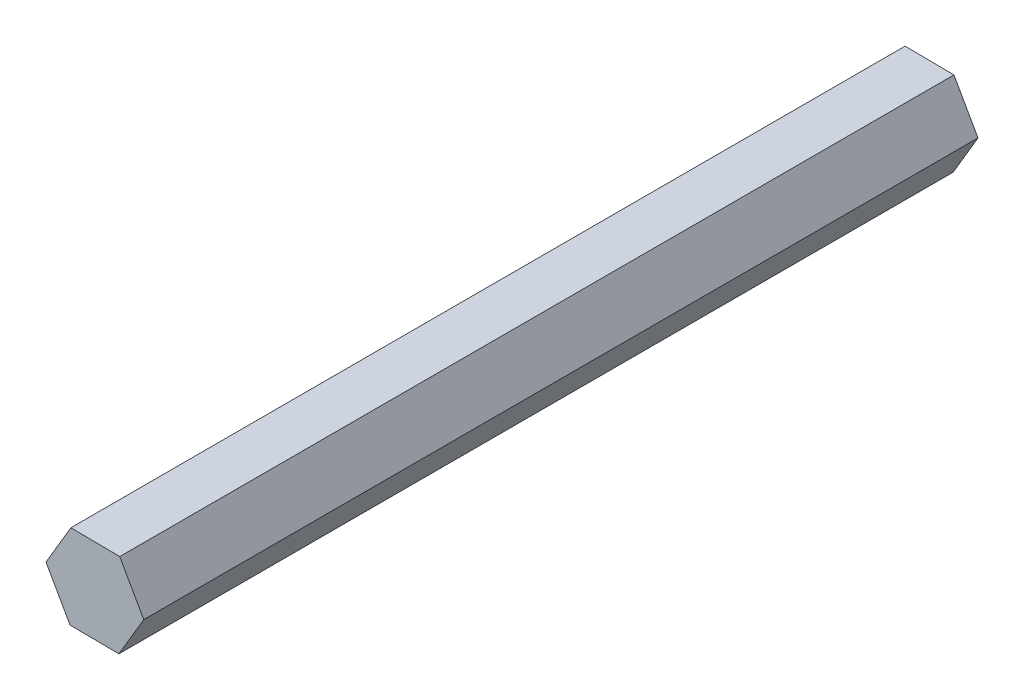
SolidWorks part; units mm, degrees
ref_plane "Front Plane" through (0, 0, 0) normal (0, 0, 1) x (1, 0, 0)
ref_plane "Top Plane" through (0, 0, 0) normal (0, 1, 0) x (1, 0, 0)
ref_plane "Right Plane" through (0, 0, 0) normal (1, 0, 0) x (0, 0, -1)
sketch "Sketch1" plane through (0, 0, 0) normal (0, 0, 1) x (1, 0, 0)
  line L1 (-2.353, -1.3662) -> (-0.9794, 0.9606)
  line L2 (-0.9794, 0.9606) -> (-2.3077, 3.3135)
  line L3 (-2.3077, 3.3135) -> (-5.0095, 3.3397)
  line L4 (-5.0095, 3.3397) -> (-6.3831, 1.0129)
  line L5 (-6.3831, 1.0129) -> (-5.0548, -1.3401)
  line L6 (-5.0548, -1.3401) -> (-2.353, -1.3662)
  circle A0 centre (-3.6813, 0.9867) radius 2.34 construction
  dimension "D1" = 4.68
extrude "Boss-Extrude1" add sketch "Sketch1" along normal blind 46.1
